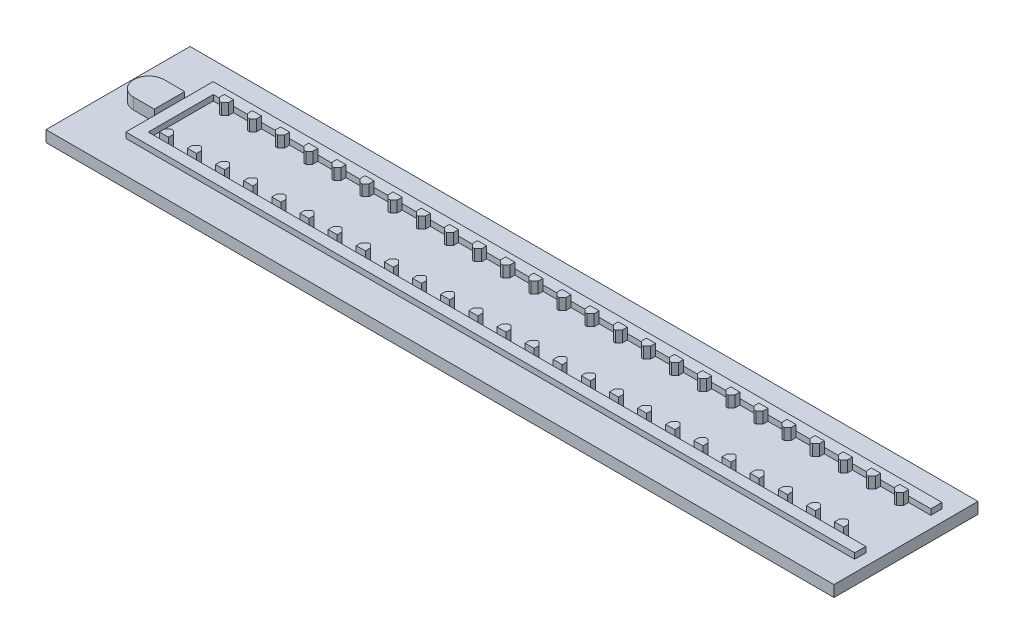
SolidWorks part; units mm, degrees
ref_plane "Front Plane" through (0, 0, 0) normal (0, 0, 1) x (1, 0, 0)
ref_plane "Top Plane" through (0, 0, 0) normal (0, 1, 0) x (1, 0, 0)
ref_plane "Right Plane" through (0, 0, 0) normal (1, 0, 0) x (0, 0, -1)
sketch "Sketch1" plane through (0, 0, 0) normal (0, 1, 0) x (1, 0, 0)
  line L0 (-40.909, -15.5054) -> (218.1261, -15.5054)
  line L1 (-36.909, -11.5614) -> (-32.9778, -11.5614)
  line L2 (-22.9778, -11.5614) -> (-29.7568, -11.5614)
  line L3 (-40.909, 15.5614) -> (218.1261, 15.5614)
  line L4 (-19.7568, -11.5614) -> (-12.9778, -11.5614)
  line L5 (-48.251, -5.3994) -> (-40.909, -5.3994)
  line L6 (-40.909, -5.3994) -> (-40.909, -15.5054)
  line L7 (-48.251, 5.3994) -> (-40.909, 5.3994)
  line L8 (-40.909, 5.3994) -> (-40.909, 15.5614)
  line L9 (-9.7568, -11.5614) -> (-2.9778, -11.5614)
  line L10 (-32.9778, -11.5614) -> (-32.9778, -9.7922)
  line L11 (-32.9778, -9.7922) -> (-31.7373, -8.5518)
  line L12 (-31.7373, -8.5518) -> (-30.9972, -8.5518)
  line L13 (-30.9972, -8.5518) -> (-29.7568, -9.7922)
  line L14 (-29.7568, -9.7922) -> (-29.7568, -11.5614)
  line L15 (-22.9778, -11.5614) -> (-22.9778, -9.7922)
  line L16 (-22.9778, -9.7922) -> (-21.7373, -8.5518)
  line L17 (-21.7373, -8.5518) -> (-20.9972, -8.5518)
  line L18 (-20.9972, -8.5518) -> (-19.7568, -9.7922)
  line L19 (-19.7568, -9.7922) -> (-19.7568, -11.5614)
  line L20 (-12.9778, -11.5614) -> (-12.9778, -9.7922)
  line L21 (-12.9778, -9.7922) -> (-11.7373, -8.5518)
  line L22 (-11.7373, -8.5518) -> (-10.9972, -8.5518)
  line L23 (-10.9972, -8.5518) -> (-9.7568, -9.7922)
  line L24 (-9.7568, -9.7922) -> (-9.7568, -11.5614)
  line L25 (-2.9778, -11.5614) -> (-2.9778, -9.7922)
  line L26 (-2.9778, -9.7922) -> (-1.7373, -8.5518)
  line L27 (-1.7373, -8.5518) -> (-0.9972, -8.5518)
  line L28 (-0.9972, -8.5518) -> (0.2432, -9.7922)
  line L29 (0.2432, -9.7922) -> (0.2432, -11.5614)
  line L30 (7.0222, -11.5614) -> (7.0222, -9.7922)
  line L31 (7.0222, -9.7922) -> (8.2627, -8.5518)
  line L32 (8.2627, -8.5518) -> (9.0028, -8.5518)
  line L33 (9.0028, -8.5518) -> (10.2432, -9.7922)
  line L34 (10.2432, -9.7922) -> (10.2432, -11.5614)
  line L35 (17.0222, -11.5614) -> (17.0222, -9.7922)
  line L36 (17.0222, -9.7922) -> (18.2627, -8.5518)
  line L37 (18.2627, -8.5518) -> (19.0028, -8.5518)
  line L38 (19.0028, -8.5518) -> (20.2432, -9.7922)
  line L39 (20.2432, -9.7922) -> (20.2432, -11.5614)
  line L40 (27.0222, -11.5614) -> (27.0222, -9.7922)
  line L41 (27.0222, -9.7922) -> (28.2627, -8.5518)
  line L42 (28.2627, -8.5518) -> (29.0028, -8.5518)
  line L43 (29.0028, -8.5518) -> (30.2432, -9.7922)
  line L44 (30.2432, -9.7922) -> (30.2432, -11.5614)
  line L45 (37.0222, -11.5614) -> (37.0222, -9.7922)
  line L46 (37.0222, -9.7922) -> (38.2627, -8.5518)
  line L47 (38.2627, -8.5518) -> (39.0028, -8.5518)
  line L48 (39.0028, -8.5518) -> (40.2432, -9.7922)
  line L49 (40.2432, -9.7922) -> (40.2432, -11.5614)
  line L50 (47.0222, -11.5614) -> (47.0222, -9.7922)
  line L51 (47.0222, -9.7922) -> (48.2627, -8.5518)
  line L52 (48.2627, -8.5518) -> (49.0028, -8.5518)
  line L53 (49.0028, -8.5518) -> (50.2432, -9.7922)
  line L54 (50.2432, -9.7922) -> (50.2432, -11.5614)
  line L55 (57.0222, -11.5614) -> (57.0222, -9.7922)
  line L56 (57.0222, -9.7922) -> (58.2627, -8.5518)
  line L57 (58.2627, -8.5518) -> (59.0028, -8.5518)
  line L58 (59.0028, -8.5518) -> (60.2432, -9.7922)
  line L59 (60.2432, -9.7922) -> (60.2432, -11.5614)
  line L60 (67.0222, -11.5614) -> (67.0222, -9.7922)
  line L61 (67.0222, -9.7922) -> (68.2627, -8.5518)
  line L62 (68.2627, -8.5518) -> (69.0028, -8.5518)
  line L63 (69.0028, -8.5518) -> (70.2432, -9.7922)
  line L64 (70.2432, -9.7922) -> (70.2432, -11.5614)
  line L65 (77.0222, -11.5614) -> (77.0222, -9.7922)
  line L66 (77.0222, -9.7922) -> (78.2627, -8.5518)
  line L67 (78.2627, -8.5518) -> (79.0028, -8.5518)
  line L68 (79.0028, -8.5518) -> (80.2432, -9.7922)
  line L69 (80.2432, -9.7922) -> (80.2432, -11.5614)
  line L70 (87.0222, -11.5614) -> (87.0222, -9.7922)
  line L71 (87.0222, -9.7922) -> (88.2627, -8.5518)
  line L72 (88.2627, -8.5518) -> (89.0028, -8.5518)
  line L73 (89.0028, -8.5518) -> (90.2432, -9.7922)
  line L74 (90.2432, -9.7922) -> (90.2432, -11.5614)
  line L75 (97.0222, -11.5614) -> (97.0222, -9.7922)
  line L76 (97.0222, -9.7922) -> (98.2627, -8.5518)
  line L77 (98.2627, -8.5518) -> (99.0028, -8.5518)
  line L78 (99.0028, -8.5518) -> (100.2432, -9.7922)
  line L79 (100.2432, -9.7922) -> (100.2432, -11.5614)
  line L80 (107.0222, -11.5614) -> (107.0222, -9.7922)
  line L81 (107.0222, -9.7922) -> (108.2627, -8.5518)
  line L82 (108.2627, -8.5518) -> (109.0028, -8.5518)
  line L83 (109.0028, -8.5518) -> (110.2432, -9.7922)
  line L84 (110.2432, -9.7922) -> (110.2432, -11.5614)
  line L85 (117.0222, -11.5614) -> (117.0222, -9.7922)
  line L86 (117.0222, -9.7922) -> (118.2627, -8.5518)
  line L87 (118.2627, -8.5518) -> (119.0028, -8.5518)
  line L88 (119.0028, -8.5518) -> (120.2432, -9.7922)
  line L89 (120.2432, -9.7922) -> (120.2432, -11.5614)
  line L90 (127.0222, -11.5614) -> (127.0222, -9.7922)
  line L91 (127.0222, -9.7922) -> (128.2627, -8.5518)
  line L92 (128.2627, -8.5518) -> (129.0028, -8.5518)
  line L93 (129.0028, -8.5518) -> (130.2432, -9.7922)
  line L94 (130.2432, -9.7922) -> (130.2432, -11.5614)
  line L95 (137.0222, -11.5614) -> (137.0222, -9.7922)
  line L96 (137.0222, -9.7922) -> (138.2627, -8.5518)
  line L97 (138.2627, -8.5518) -> (139.0028, -8.5518)
  line L98 (139.0028, -8.5518) -> (140.2432, -9.7922)
  line L99 (140.2432, -9.7922) -> (140.2432, -11.5614)
  line L100 (147.0222, -11.5614) -> (147.0222, -9.7922)
  line L101 (147.0222, -9.7922) -> (148.2627, -8.5518)
  line L102 (148.2627, -8.5518) -> (149.0028, -8.5518)
  line L103 (149.0028, -8.5518) -> (150.2432, -9.7922)
  line L104 (150.2432, -9.7922) -> (150.2432, -11.5614)
  line L105 (157.0222, -11.5614) -> (157.0222, -9.7922)
  line L106 (157.0222, -9.7922) -> (158.2627, -8.5518)
  line L107 (158.2627, -8.5518) -> (159.0028, -8.5518)
  line L108 (159.0028, -8.5518) -> (160.2432, -9.7922)
  line L109 (160.2432, -9.7922) -> (160.2432, -11.5614)
  line L110 (167.0222, -11.5614) -> (167.0222, -9.7922)
  line L111 (167.0222, -9.7922) -> (168.2627, -8.5518)
  line L112 (168.2627, -8.5518) -> (169.0028, -8.5518)
  line L113 (169.0028, -8.5518) -> (170.2432, -9.7922)
  line L114 (170.2432, -9.7922) -> (170.2432, -11.5614)
  line L115 (177.0222, -11.5614) -> (177.0222, -9.7922)
  line L116 (177.0222, -9.7922) -> (178.2627, -8.5518)
  line L117 (178.2627, -8.5518) -> (179.0028, -8.5518)
  line L118 (179.0028, -8.5518) -> (180.2432, -9.7922)
  line L119 (180.2432, -9.7922) -> (180.2432, -11.5614)
  line L120 (187.0222, -11.5614) -> (187.0222, -9.7922)
  line L121 (187.0222, -9.7922) -> (188.2627, -8.5518)
  line L122 (188.2627, -8.5518) -> (189.0028, -8.5518)
  line L123 (189.0028, -8.5518) -> (190.2432, -9.7922)
  line L124 (190.2432, -9.7922) -> (190.2432, -11.5614)
  line L125 (197.0222, -11.5614) -> (197.0222, -9.7922)
  line L126 (197.0222, -9.7922) -> (198.2627, -8.5518)
  line L127 (198.2627, -8.5518) -> (199.0028, -8.5518)
  line L128 (199.0028, -8.5518) -> (200.2432, -9.7922)
  line L129 (200.2432, -9.7922) -> (200.2432, -11.5614)
  line L130 (207.0222, -11.5614) -> (207.0222, -9.7922)
  line L131 (207.0222, -9.7922) -> (208.2627, -8.5518)
  line L132 (208.2627, -8.5518) -> (209.0028, -8.5518)
  line L133 (209.0028, -8.5518) -> (210.2432, -9.7922)
  line L134 (210.2432, -9.7922) -> (210.2432, -11.5614)
  line L135 (218.1261, -11.5614) -> (218.1261, -15.5054)
  line L136 (210.2432, 9.7922) -> (210.2432, 11.5614)
  line L137 (209.0028, 8.5518) -> (210.2432, 9.7922)
  line L138 (208.2627, 8.5518) -> (209.0028, 8.5518)
  line L139 (207.0222, 9.7922) -> (208.2627, 8.5518)
  line L140 (207.0222, 11.5614) -> (207.0222, 9.7922)
  line L141 (200.2432, 9.7922) -> (200.2432, 11.5614)
  line L142 (199.0028, 8.5518) -> (200.2432, 9.7922)
  line L143 (198.2627, 8.5518) -> (199.0028, 8.5518)
  line L144 (197.0222, 9.7922) -> (198.2627, 8.5518)
  line L145 (197.0222, 11.5614) -> (197.0222, 9.7922)
  line L146 (190.2432, 9.7922) -> (190.2432, 11.5614)
  line L147 (189.0028, 8.5518) -> (190.2432, 9.7922)
  line L148 (188.2627, 8.5518) -> (189.0028, 8.5518)
  line L149 (187.0222, 9.7922) -> (188.2627, 8.5518)
  line L150 (187.0222, 11.5614) -> (187.0222, 9.7922)
  line L151 (180.2432, 9.7922) -> (180.2432, 11.5614)
  line L152 (179.0028, 8.5518) -> (180.2432, 9.7922)
  line L153 (178.2627, 8.5518) -> (179.0028, 8.5518)
  line L154 (177.0222, 9.7922) -> (178.2627, 8.5518)
  line L155 (177.0222, 11.5614) -> (177.0222, 9.7922)
  line L156 (170.2432, 9.7922) -> (170.2432, 11.5614)
  line L157 (169.0028, 8.5518) -> (170.2432, 9.7922)
  line L158 (168.2627, 8.5518) -> (169.0028, 8.5518)
  line L159 (167.0222, 9.7922) -> (168.2627, 8.5518)
  line L160 (167.0222, 11.5614) -> (167.0222, 9.7922)
  line L161 (160.2432, 9.7922) -> (160.2432, 11.5614)
  line L162 (159.0028, 8.5518) -> (160.2432, 9.7922)
  line L163 (158.2627, 8.5518) -> (159.0028, 8.5518)
  line L164 (157.0222, 9.7922) -> (158.2627, 8.5518)
  line L165 (157.0222, 11.5614) -> (157.0222, 9.7922)
  line L166 (150.2432, 9.7922) -> (150.2432, 11.5614)
  line L167 (149.0028, 8.5518) -> (150.2432, 9.7922)
  line L168 (148.2627, 8.5518) -> (149.0028, 8.5518)
  line L169 (147.0222, 9.7922) -> (148.2627, 8.5518)
  line L170 (147.0222, 11.5614) -> (147.0222, 9.7922)
  line L171 (140.2432, 9.7922) -> (140.2432, 11.5614)
  line L172 (139.0028, 8.5518) -> (140.2432, 9.7922)
  line L173 (138.2627, 8.5518) -> (139.0028, 8.5518)
  line L174 (137.0222, 9.7922) -> (138.2627, 8.5518)
  line L175 (137.0222, 11.5614) -> (137.0222, 9.7922)
  line L176 (130.2432, 9.7922) -> (130.2432, 11.5614)
  line L177 (129.0028, 8.5518) -> (130.2432, 9.7922)
  line L178 (128.2627, 8.5518) -> (129.0028, 8.5518)
  line L179 (127.0222, 9.7922) -> (128.2627, 8.5518)
  line L180 (127.0222, 11.5614) -> (127.0222, 9.7922)
  line L181 (120.2432, 9.7922) -> (120.2432, 11.5614)
  line L182 (119.0028, 8.5518) -> (120.2432, 9.7922)
  line L183 (118.2627, 8.5518) -> (119.0028, 8.5518)
  line L184 (117.0222, 9.7922) -> (118.2627, 8.5518)
  line L185 (117.0222, 11.5614) -> (117.0222, 9.7922)
  line L186 (110.2432, 9.7922) -> (110.2432, 11.5614)
  line L187 (109.0028, 8.5518) -> (110.2432, 9.7922)
  line L188 (108.2627, 8.5518) -> (109.0028, 8.5518)
  line L189 (107.0222, 9.7922) -> (108.2627, 8.5518)
  line L190 (107.0222, 11.5614) -> (107.0222, 9.7922)
  line L191 (100.2432, 9.7922) -> (100.2432, 11.5614)
  line L192 (99.0028, 8.5518) -> (100.2432, 9.7922)
  line L193 (98.2627, 8.5518) -> (99.0028, 8.5518)
  line L194 (97.0222, 9.7922) -> (98.2627, 8.5518)
  line L195 (97.0222, 11.5614) -> (97.0222, 9.7922)
  line L196 (90.2432, 9.7922) -> (90.2432, 11.5614)
  line L197 (89.0028, 8.5518) -> (90.2432, 9.7922)
  line L198 (88.2627, 8.5518) -> (89.0028, 8.5518)
  line L199 (87.0222, 9.7922) -> (88.2627, 8.5518)
  line L200 (87.0222, 11.5614) -> (87.0222, 9.7922)
  line L201 (80.2432, 9.7922) -> (80.2432, 11.5614)
  line L202 (79.0028, 8.5518) -> (80.2432, 9.7922)
  line L203 (78.2627, 8.5518) -> (79.0028, 8.5518)
  line L204 (77.0222, 9.7922) -> (78.2627, 8.5518)
  line L205 (77.0222, 11.5614) -> (77.0222, 9.7922)
  line L206 (70.2432, 9.7922) -> (70.2432, 11.5614)
  line L207 (69.0028, 8.5518) -> (70.2432, 9.7922)
  line L208 (68.2627, 8.5518) -> (69.0028, 8.5518)
  line L209 (67.0222, 9.7922) -> (68.2627, 8.5518)
  line L210 (67.0222, 11.5614) -> (67.0222, 9.7922)
  line L211 (60.2432, 9.7922) -> (60.2432, 11.5614)
  line L212 (59.0028, 8.5518) -> (60.2432, 9.7922)
  line L213 (58.2627, 8.5518) -> (59.0028, 8.5518)
  line L214 (57.0222, 9.7922) -> (58.2627, 8.5518)
  line L215 (57.0222, 11.5614) -> (57.0222, 9.7922)
  line L216 (50.2432, 9.7922) -> (50.2432, 11.5614)
  line L217 (49.0028, 8.5518) -> (50.2432, 9.7922)
  line L218 (48.2627, 8.5518) -> (49.0028, 8.5518)
  line L219 (47.0222, 9.7922) -> (48.2627, 8.5518)
  line L220 (47.0222, 11.5614) -> (47.0222, 9.7922)
  line L221 (40.2432, 9.7922) -> (40.2432, 11.5614)
  line L222 (39.0028, 8.5518) -> (40.2432, 9.7922)
  line L223 (38.2627, 8.5518) -> (39.0028, 8.5518)
  line L224 (37.0222, 9.7922) -> (38.2627, 8.5518)
  line L225 (37.0222, 11.5614) -> (37.0222, 9.7922)
  line L226 (30.2432, 9.7922) -> (30.2432, 11.5614)
  line L227 (29.0028, 8.5518) -> (30.2432, 9.7922)
  line L228 (28.2627, 8.5518) -> (29.0028, 8.5518)
  line L229 (27.0222, 9.7922) -> (28.2627, 8.5518)
  line L230 (27.0222, 11.5614) -> (27.0222, 9.7922)
  line L231 (20.2432, 9.7922) -> (20.2432, 11.5614)
  line L232 (19.0028, 8.5518) -> (20.2432, 9.7922)
  line L233 (18.2627, 8.5518) -> (19.0028, 8.5518)
  line L234 (17.0222, 9.7922) -> (18.2627, 8.5518)
  line L235 (17.0222, 11.5614) -> (17.0222, 9.7922)
  line L236 (10.2432, 9.7922) -> (10.2432, 11.5614)
  line L237 (9.0028, 8.5518) -> (10.2432, 9.7922)
  line L238 (8.2627, 8.5518) -> (9.0028, 8.5518)
  line L239 (7.0222, 9.7922) -> (8.2627, 8.5518)
  line L240 (7.0222, 11.5614) -> (7.0222, 9.7922)
  line L241 (0.2432, 9.7922) -> (0.2432, 11.5614)
  line L242 (-0.9972, 8.5518) -> (0.2432, 9.7922)
  line L243 (-1.7373, 8.5518) -> (-0.9972, 8.5518)
  line L244 (-2.9778, 9.7922) -> (-1.7373, 8.5518)
  line L245 (-2.9778, 11.5614) -> (-2.9778, 9.7922)
  line L246 (-9.7568, 9.7922) -> (-9.7568, 11.5614)
  line L247 (-10.9972, 8.5518) -> (-9.7568, 9.7922)
  line L248 (-11.7373, 8.5518) -> (-10.9972, 8.5518)
  line L249 (-12.9778, 9.7922) -> (-11.7373, 8.5518)
  line L250 (-12.9778, 11.5614) -> (-12.9778, 9.7922)
  line L251 (-19.7568, 9.7922) -> (-19.7568, 11.5614)
  line L252 (-20.9972, 8.5518) -> (-19.7568, 9.7922)
  line L253 (-21.7373, 8.5518) -> (-20.9972, 8.5518)
  line L254 (-22.9778, 9.7922) -> (-21.7373, 8.5518)
  line L255 (-22.9778, 11.5614) -> (-22.9778, 9.7922)
  line L256 (-29.7568, 9.7922) -> (-29.7568, 11.5614)
  line L257 (-30.9972, 8.5518) -> (-29.7568, 9.7922)
  line L258 (-31.7373, 8.5518) -> (-30.9972, 8.5518)
  line L259 (-32.9778, 9.7922) -> (-31.7373, 8.5518)
  line L260 (-32.9778, 11.5614) -> (-32.9778, 9.7922)
  line L261 (-36.909, 11.5614) -> (-36.909, -11.5614)
  line L262 (-40.909, 5.3994) -> (-40.909, 15.5614)
  line L264 (-40.909, 15.5614) -> (218.1261, 15.5614)
  line L265 (218.1261, 11.5614) -> (218.1261, 15.5614)
  line L266 (-12.9778, -11.5614) -> (-19.7568, -11.5614)
  line L267 (0.2432, -11.5614) -> (7.0222, -11.5614)
  line L268 (-2.9778, -11.5614) -> (-9.7568, -11.5614)
  line L269 (10.2432, -11.5614) -> (17.0222, -11.5614)
  line L270 (7.0222, -11.5614) -> (0.2432, -11.5614)
  line L271 (20.2432, -11.5614) -> (27.0222, -11.5614)
  line L272 (17.0222, -11.5614) -> (10.2432, -11.5614)
  line L273 (30.2432, -11.5614) -> (37.0222, -11.5614)
  line L274 (27.0222, -11.5614) -> (20.2432, -11.5614)
  line L275 (40.2432, -11.5614) -> (47.0222, -11.5614)
  line L276 (37.0222, -11.5614) -> (30.2432, -11.5614)
  line L277 (50.2432, -11.5614) -> (57.0222, -11.5614)
  line L278 (47.0222, -11.5614) -> (40.2432, -11.5614)
  line L279 (60.2432, -11.5614) -> (67.0222, -11.5614)
  line L280 (57.0222, -11.5614) -> (50.2432, -11.5614)
  line L281 (70.2432, -11.5614) -> (77.0222, -11.5614)
  line L282 (67.0222, -11.5614) -> (60.2432, -11.5614)
  line L283 (80.2432, -11.5614) -> (87.0222, -11.5614)
  line L284 (77.0222, -11.5614) -> (70.2432, -11.5614)
  line L285 (90.2432, -11.5614) -> (97.0222, -11.5614)
  line L286 (87.0222, -11.5614) -> (80.2432, -11.5614)
  line L287 (100.2432, -11.5614) -> (107.0222, -11.5614)
  line L288 (97.0222, -11.5614) -> (90.2432, -11.5614)
  line L289 (110.2432, -11.5614) -> (117.0222, -11.5614)
  line L290 (107.0222, -11.5614) -> (100.2432, -11.5614)
  line L291 (120.2432, -11.5614) -> (127.0222, -11.5614)
  line L292 (117.0222, -11.5614) -> (110.2432, -11.5614)
  line L293 (130.2432, -11.5614) -> (137.0222, -11.5614)
  line L294 (127.0222, -11.5614) -> (120.2432, -11.5614)
  line L295 (140.2432, -11.5614) -> (147.0222, -11.5614)
  line L296 (137.0222, -11.5614) -> (130.2432, -11.5614)
  line L297 (150.2432, -11.5614) -> (157.0222, -11.5614)
  line L298 (147.0222, -11.5614) -> (140.2432, -11.5614)
  line L299 (160.2432, -11.5614) -> (167.0222, -11.5614)
  line L300 (157.0222, -11.5614) -> (150.2432, -11.5614)
  line L301 (170.2432, -11.5614) -> (177.0222, -11.5614)
  line L302 (167.0222, -11.5614) -> (160.2432, -11.5614)
  line L303 (180.2432, -11.5614) -> (187.0222, -11.5614)
  line L304 (177.0222, -11.5614) -> (170.2432, -11.5614)
  line L305 (190.2432, -11.5614) -> (197.0222, -11.5614)
  line L306 (187.0222, -11.5614) -> (180.2432, -11.5614)
  line L307 (200.2432, -11.5614) -> (207.0222, -11.5614)
  line L308 (197.0222, -11.5614) -> (190.2432, -11.5614)
  line L309 (210.2432, -11.5614) -> (217.0222, -11.5614)
  line L310 (207.0222, -11.5614) -> (200.2432, -11.5614)
  line L311 (217.0222, -11.5614) -> (218.1261, -11.5614)
  line L312 (217.0222, -11.5614) -> (210.2432, -11.5614)
  line L313 (220.2432, -11.5614) -> (227.0222, -11.5614) [skipped]
  line L315 (217.0222, 11.5054) -> (210.2432, 11.5054)
  line L316 (217.0222, 11.5054) -> (218.1261, 11.5054)
  line L317 (207.0222, 11.5054) -> (200.2432, 11.5054)
  line L318 (210.2432, 11.5054) -> (217.0222, 11.5054)
  line L319 (197.0222, 11.5054) -> (190.2432, 11.5054)
  line L320 (200.2432, 11.5054) -> (207.0222, 11.5054)
  line L321 (187.0222, 11.5054) -> (180.2432, 11.5054)
  line L322 (190.2432, 11.5054) -> (197.0222, 11.5054)
  line L323 (177.0222, 11.5054) -> (170.2432, 11.5054)
  line L324 (180.2432, 11.5054) -> (187.0222, 11.5054)
  line L325 (167.0222, 11.5054) -> (160.2432, 11.5054)
  line L326 (170.2432, 11.5054) -> (177.0222, 11.5054)
  line L327 (157.0222, 11.5054) -> (150.2432, 11.5054)
  line L328 (160.2432, 11.5054) -> (167.0222, 11.5054)
  line L329 (147.0222, 11.5054) -> (140.2432, 11.5054)
  line L330 (150.2432, 11.5054) -> (157.0222, 11.5054)
  line L331 (137.0222, 11.5054) -> (130.2432, 11.5054)
  line L332 (140.2432, 11.5054) -> (147.0222, 11.5054)
  line L333 (127.0222, 11.5054) -> (120.2432, 11.5054)
  line L334 (130.2432, 11.5054) -> (137.0222, 11.5054)
  line L335 (117.0222, 11.5054) -> (110.2432, 11.5054)
  line L336 (120.2432, 11.5054) -> (127.0222, 11.5054)
  line L337 (107.0222, 11.5054) -> (100.2432, 11.5054)
  line L338 (110.2432, 11.5054) -> (117.0222, 11.5054)
  line L339 (97.0222, 11.5054) -> (90.2432, 11.5054)
  line L340 (100.2432, 11.5054) -> (107.0222, 11.5054)
  line L341 (87.0222, 11.5054) -> (80.2432, 11.5054)
  line L342 (90.2432, 11.5054) -> (97.0222, 11.5054)
  line L343 (77.0222, 11.5054) -> (70.2432, 11.5054)
  line L344 (80.2432, 11.5054) -> (87.0222, 11.5054)
  line L345 (67.0222, 11.5054) -> (60.2432, 11.5054)
  line L346 (70.2432, 11.5054) -> (77.0222, 11.5054)
  line L347 (57.0222, 11.5054) -> (50.2432, 11.5054)
  line L348 (60.2432, 11.5054) -> (67.0222, 11.5054)
  line L349 (47.0222, 11.5054) -> (40.2432, 11.5054)
  line L350 (50.2432, 11.5054) -> (57.0222, 11.5054)
  line L351 (37.0222, 11.5054) -> (30.2432, 11.5054)
  line L352 (40.2432, 11.5054) -> (47.0222, 11.5054)
  line L353 (27.0222, 11.5054) -> (20.2432, 11.5054)
  line L354 (30.2432, 11.5054) -> (37.0222, 11.5054)
  line L355 (17.0222, 11.5054) -> (10.2432, 11.5054)
  line L356 (20.2432, 11.5054) -> (27.0222, 11.5054)
  line L357 (7.0222, 11.5054) -> (0.2432, 11.5054)
  line L358 (10.2432, 11.5054) -> (17.0222, 11.5054)
  line L359 (-2.9778, 11.5054) -> (-9.7568, 11.5054)
  line L360 (0.2432, 11.5054) -> (7.0222, 11.5054)
  line L361 (-12.9778, 11.5054) -> (-19.7568, 11.5054)
  line L362 (-36.909, -11.5614) -> (-36.909, 11.5054)
  line L363 (218.1261, 11.5054) -> (218.1261, 15.5054)
  line L364 (210.2432, 9.7922) -> (210.2432, 11.5054)
  line L365 (209.0028, 8.5518) -> (210.2432, 9.7922)
  line L366 (208.2627, 8.5518) -> (209.0028, 8.5518)
  line L367 (207.0222, 9.7922) -> (208.2627, 8.5518)
  line L368 (207.0222, 11.5054) -> (207.0222, 9.7922)
  line L369 (200.2432, 9.7922) -> (200.2432, 11.5054)
  line L370 (199.0028, 8.5518) -> (200.2432, 9.7922)
  line L371 (198.2627, 8.5518) -> (199.0028, 8.5518)
  line L372 (197.0222, 9.7922) -> (198.2627, 8.5518)
  line L373 (197.0222, 11.5054) -> (197.0222, 9.7922)
  line L374 (190.2432, 9.7922) -> (190.2432, 11.5054)
  line L375 (189.0028, 8.5518) -> (190.2432, 9.7922)
  line L376 (188.2627, 8.5518) -> (189.0028, 8.5518)
  line L377 (187.0222, 9.7922) -> (188.2627, 8.5518)
  line L378 (187.0222, 11.5054) -> (187.0222, 9.7922)
  line L379 (180.2432, 9.7922) -> (180.2432, 11.5054)
  line L380 (179.0028, 8.5518) -> (180.2432, 9.7922)
  line L381 (178.2627, 8.5518) -> (179.0028, 8.5518)
  line L382 (177.0222, 9.7922) -> (178.2627, 8.5518)
  line L383 (177.0222, 11.5054) -> (177.0222, 9.7922)
  line L384 (170.2432, 9.7922) -> (170.2432, 11.5054)
  line L385 (169.0028, 8.5518) -> (170.2432, 9.7922)
  line L386 (168.2627, 8.5518) -> (169.0028, 8.5518)
  line L387 (167.0222, 9.7922) -> (168.2627, 8.5518)
  line L388 (167.0222, 11.5054) -> (167.0222, 9.7922)
  line L389 (160.2432, 9.7922) -> (160.2432, 11.5054)
  line L390 (159.0028, 8.5518) -> (160.2432, 9.7922)
  line L391 (158.2627, 8.5518) -> (159.0028, 8.5518)
  line L392 (157.0222, 9.7922) -> (158.2627, 8.5518)
  line L393 (157.0222, 11.5054) -> (157.0222, 9.7922)
  line L394 (150.2432, 9.7922) -> (150.2432, 11.5054)
  line L395 (149.0028, 8.5518) -> (150.2432, 9.7922)
  line L396 (148.2627, 8.5518) -> (149.0028, 8.5518)
  line L397 (147.0222, 9.7922) -> (148.2627, 8.5518)
  line L398 (147.0222, 11.5054) -> (147.0222, 9.7922)
  line L399 (140.2432, 9.7922) -> (140.2432, 11.5054)
  line L400 (139.0028, 8.5518) -> (140.2432, 9.7922)
  line L401 (138.2627, 8.5518) -> (139.0028, 8.5518)
  line L402 (137.0222, 9.7922) -> (138.2627, 8.5518)
  line L403 (137.0222, 11.5054) -> (137.0222, 9.7922)
  line L404 (130.2432, 9.7922) -> (130.2432, 11.5054)
  line L405 (129.0028, 8.5518) -> (130.2432, 9.7922)
  line L406 (128.2627, 8.5518) -> (129.0028, 8.5518)
  line L407 (127.0222, 9.7922) -> (128.2627, 8.5518)
  line L408 (127.0222, 11.5054) -> (127.0222, 9.7922)
  line L409 (120.2432, 9.7922) -> (120.2432, 11.5054)
  line L410 (119.0028, 8.5518) -> (120.2432, 9.7922)
  line L411 (118.2627, 8.5518) -> (119.0028, 8.5518)
  line L412 (117.0222, 9.7922) -> (118.2627, 8.5518)
  line L413 (117.0222, 11.5054) -> (117.0222, 9.7922)
  line L414 (110.2432, 9.7922) -> (110.2432, 11.5054)
  line L415 (109.0028, 8.5518) -> (110.2432, 9.7922)
  line L416 (108.2627, 8.5518) -> (109.0028, 8.5518)
  line L417 (107.0222, 9.7922) -> (108.2627, 8.5518)
  line L418 (107.0222, 11.5054) -> (107.0222, 9.7922)
  line L419 (100.2432, 9.7922) -> (100.2432, 11.5054)
  line L420 (99.0028, 8.5518) -> (100.2432, 9.7922)
  line L421 (98.2627, 8.5518) -> (99.0028, 8.5518)
  line L422 (97.0222, 9.7922) -> (98.2627, 8.5518)
  line L423 (97.0222, 11.5054) -> (97.0222, 9.7922)
  line L424 (90.2432, 9.7922) -> (90.2432, 11.5054)
  line L425 (89.0028, 8.5518) -> (90.2432, 9.7922)
  line L426 (88.2627, 8.5518) -> (89.0028, 8.5518)
  line L427 (87.0222, 9.7922) -> (88.2627, 8.5518)
  line L428 (87.0222, 11.5054) -> (87.0222, 9.7922)
  line L429 (80.2432, 9.7922) -> (80.2432, 11.5054)
  line L430 (79.0028, 8.5518) -> (80.2432, 9.7922)
  line L431 (78.2627, 8.5518) -> (79.0028, 8.5518)
  line L432 (77.0222, 9.7922) -> (78.2627, 8.5518)
  line L433 (77.0222, 11.5054) -> (77.0222, 9.7922)
  line L434 (70.2432, 9.7922) -> (70.2432, 11.5054)
  line L435 (69.0028, 8.5518) -> (70.2432, 9.7922)
  line L436 (68.2627, 8.5518) -> (69.0028, 8.5518)
  line L437 (67.0222, 9.7922) -> (68.2627, 8.5518)
  line L438 (67.0222, 11.5054) -> (67.0222, 9.7922)
  line L439 (60.2432, 9.7922) -> (60.2432, 11.5054)
  line L440 (59.0028, 8.5518) -> (60.2432, 9.7922)
  line L441 (58.2627, 8.5518) -> (59.0028, 8.5518)
  line L442 (57.0222, 9.7922) -> (58.2627, 8.5518)
  line L443 (57.0222, 11.5054) -> (57.0222, 9.7922)
  line L444 (50.2432, 9.7922) -> (50.2432, 11.5054)
  line L445 (49.0028, 8.5518) -> (50.2432, 9.7922)
  line L446 (48.2627, 8.5518) -> (49.0028, 8.5518)
  line L447 (47.0222, 9.7922) -> (48.2627, 8.5518)
  line L448 (47.0222, 11.5054) -> (47.0222, 9.7922)
  line L449 (40.2432, 9.7922) -> (40.2432, 11.5054)
  line L450 (39.0028, 8.5518) -> (40.2432, 9.7922)
  line L451 (38.2627, 8.5518) -> (39.0028, 8.5518)
  line L452 (37.0222, 9.7922) -> (38.2627, 8.5518)
  line L453 (37.0222, 11.5054) -> (37.0222, 9.7922)
  line L454 (30.2432, 9.7922) -> (30.2432, 11.5054)
  line L455 (29.0028, 8.5518) -> (30.2432, 9.7922)
  line L456 (28.2627, 8.5518) -> (29.0028, 8.5518)
  line L457 (27.0222, 9.7922) -> (28.2627, 8.5518)
  line L458 (27.0222, 11.5054) -> (27.0222, 9.7922)
  line L459 (20.2432, 9.7922) -> (20.2432, 11.5054)
  line L460 (19.0028, 8.5518) -> (20.2432, 9.7922)
  line L461 (18.2627, 8.5518) -> (19.0028, 8.5518)
  line L462 (17.0222, 9.7922) -> (18.2627, 8.5518)
  line L463 (17.0222, 11.5054) -> (17.0222, 9.7922)
  line L464 (10.2432, 9.7922) -> (10.2432, 11.5054)
  line L465 (9.0028, 8.5518) -> (10.2432, 9.7922)
  line L466 (8.2627, 8.5518) -> (9.0028, 8.5518)
  line L467 (7.0222, 9.7922) -> (8.2627, 8.5518)
  line L468 (7.0222, 11.5054) -> (7.0222, 9.7922)
  line L469 (0.2432, 9.7922) -> (0.2432, 11.5054)
  line L470 (-0.9972, 8.5518) -> (0.2432, 9.7922)
  line L471 (-1.7373, 8.5518) -> (-0.9972, 8.5518)
  line L472 (-2.9778, 9.7922) -> (-1.7373, 8.5518)
  line L473 (-2.9778, 11.5054) -> (-2.9778, 9.7922)
  line L474 (-9.7568, 9.7922) -> (-9.7568, 11.5054)
  line L475 (-10.9972, 8.5518) -> (-9.7568, 9.7922)
  line L476 (-11.7373, 8.5518) -> (-10.9972, 8.5518)
  line L477 (-12.9778, 9.7922) -> (-11.7373, 8.5518)
  line L478 (-12.9778, 11.5054) -> (-12.9778, 9.7922)
  line L479 (-19.7568, 9.7922) -> (-19.7568, 11.5054)
  line L480 (-20.9972, 8.5518) -> (-19.7568, 9.7922)
  line L481 (-21.7373, 8.5518) -> (-20.9972, 8.5518)
  line L482 (-22.9778, 9.7922) -> (-21.7373, 8.5518)
  line L483 (-22.9778, 11.5054) -> (-22.9778, 9.7922)
  line L484 (-29.7568, 9.7922) -> (-29.7568, 11.5054)
  line L485 (-30.9972, 8.5518) -> (-29.7568, 9.7922)
  line L486 (-31.7373, 8.5518) -> (-30.9972, 8.5518)
  line L487 (-32.9778, 9.7922) -> (-31.7373, 8.5518)
  line L488 (-32.9778, 11.5054) -> (-32.9778, 9.7922)
  line L489 (-9.7568, 11.5054) -> (-2.9778, 11.5054)
  line L490 (-40.909, 5.3994) -> (-40.909, 15.5054)
  line L491 (-19.7568, 11.5054) -> (-12.9778, 11.5054)
  line L492 (-22.9778, 11.5054) -> (-29.7568, 11.5054)
  line L493 (-36.909, 11.5054) -> (-32.9778, 11.5054)
  line L494 (-40.909, 15.5054) -> (218.1261, 15.5054)
  line L495 (-36.909, 11.5614) -> (-36.909, -11.5054)
  line L496 (217.0222, 11.5614) -> (210.2432, 11.5614)
  line L497 (217.0222, 11.5614) -> (218.1261, 11.5614)
  line L498 (207.0222, 11.5614) -> (200.2432, 11.5614)
  line L499 (210.2432, 11.5614) -> (217.0222, 11.5614)
  line L500 (197.0222, 11.5614) -> (190.2432, 11.5614)
  line L501 (200.2432, 11.5614) -> (207.0222, 11.5614)
  line L502 (187.0222, 11.5614) -> (180.2432, 11.5614)
  line L503 (190.2432, 11.5614) -> (197.0222, 11.5614)
  line L504 (177.0222, 11.5614) -> (170.2432, 11.5614)
  line L505 (180.2432, 11.5614) -> (187.0222, 11.5614)
  line L506 (167.0222, 11.5614) -> (160.2432, 11.5614)
  line L507 (170.2432, 11.5614) -> (177.0222, 11.5614)
  line L508 (157.0222, 11.5614) -> (150.2432, 11.5614)
  line L509 (160.2432, 11.5614) -> (167.0222, 11.5614)
  line L510 (147.0222, 11.5614) -> (140.2432, 11.5614)
  line L511 (150.2432, 11.5614) -> (157.0222, 11.5614)
  line L512 (137.0222, 11.5614) -> (130.2432, 11.5614)
  line L513 (140.2432, 11.5614) -> (147.0222, 11.5614)
  line L514 (127.0222, 11.5614) -> (120.2432, 11.5614)
  line L515 (130.2432, 11.5614) -> (137.0222, 11.5614)
  line L516 (117.0222, 11.5614) -> (110.2432, 11.5614)
  line L517 (120.2432, 11.5614) -> (127.0222, 11.5614)
  line L518 (107.0222, 11.5614) -> (100.2432, 11.5614)
  line L519 (110.2432, 11.5614) -> (117.0222, 11.5614)
  line L520 (97.0222, 11.5614) -> (90.2432, 11.5614)
  line L521 (100.2432, 11.5614) -> (107.0222, 11.5614)
  line L522 (87.0222, 11.5614) -> (80.2432, 11.5614)
  line L523 (90.2432, 11.5614) -> (97.0222, 11.5614)
  line L524 (77.0222, 11.5614) -> (70.2432, 11.5614)
  line L525 (80.2432, 11.5614) -> (87.0222, 11.5614)
  line L526 (67.0222, 11.5614) -> (60.2432, 11.5614)
  line L527 (70.2432, 11.5614) -> (77.0222, 11.5614)
  line L528 (57.0222, 11.5614) -> (50.2432, 11.5614)
  line L529 (60.2432, 11.5614) -> (67.0222, 11.5614)
  line L530 (47.0222, 11.5614) -> (40.2432, 11.5614)
  line L531 (50.2432, 11.5614) -> (57.0222, 11.5614)
  line L532 (37.0222, 11.5614) -> (30.2432, 11.5614)
  line L533 (40.2432, 11.5614) -> (47.0222, 11.5614)
  line L534 (27.0222, 11.5614) -> (20.2432, 11.5614)
  line L535 (30.2432, 11.5614) -> (37.0222, 11.5614)
  line L536 (17.0222, 11.5614) -> (10.2432, 11.5614)
  line L537 (20.2432, 11.5614) -> (27.0222, 11.5614)
  line L538 (7.0222, 11.5614) -> (0.2432, 11.5614)
  line L539 (10.2432, 11.5614) -> (17.0222, 11.5614)
  line L540 (-2.9778, 11.5614) -> (-9.7568, 11.5614)
  line L541 (0.2432, 11.5614) -> (7.0222, 11.5614)
  line L542 (-12.9778, 11.5614) -> (-19.7568, 11.5614)
  line L543 (218.1261, 11.5614) -> (218.1261, 15.5054)
  line L544 (210.2432, 9.7922) -> (210.2432, 11.5614)
  line L545 (209.0028, 8.5518) -> (210.2432, 9.7922)
  line L546 (208.2627, 8.5518) -> (209.0028, 8.5518)
  line L547 (207.0222, 9.7922) -> (208.2627, 8.5518)
  line L548 (207.0222, 11.5614) -> (207.0222, 9.7922)
  line L549 (200.2432, 9.7922) -> (200.2432, 11.5614)
  line L550 (199.0028, 8.5518) -> (200.2432, 9.7922)
  line L551 (198.2627, 8.5518) -> (199.0028, 8.5518)
  line L552 (197.0222, 9.7922) -> (198.2627, 8.5518)
  line L553 (197.0222, 11.5614) -> (197.0222, 9.7922)
  line L554 (190.2432, 9.7922) -> (190.2432, 11.5614)
  line L555 (189.0028, 8.5518) -> (190.2432, 9.7922)
  line L556 (188.2627, 8.5518) -> (189.0028, 8.5518)
  line L557 (187.0222, 9.7922) -> (188.2627, 8.5518)
  line L558 (187.0222, 11.5614) -> (187.0222, 9.7922)
  line L559 (180.2432, 9.7922) -> (180.2432, 11.5614)
  line L560 (179.0028, 8.5518) -> (180.2432, 9.7922)
  line L561 (178.2627, 8.5518) -> (179.0028, 8.5518)
  line L562 (177.0222, 9.7922) -> (178.2627, 8.5518)
  line L563 (177.0222, 11.5614) -> (177.0222, 9.7922)
  line L564 (170.2432, 9.7922) -> (170.2432, 11.5614)
  line L565 (169.0028, 8.5518) -> (170.2432, 9.7922)
  line L566 (168.2627, 8.5518) -> (169.0028, 8.5518)
  line L567 (167.0222, 9.7922) -> (168.2627, 8.5518)
  line L568 (167.0222, 11.5614) -> (167.0222, 9.7922)
  line L569 (160.2432, 9.7922) -> (160.2432, 11.5614)
  line L570 (159.0028, 8.5518) -> (160.2432, 9.7922)
  line L571 (158.2627, 8.5518) -> (159.0028, 8.5518)
  line L572 (157.0222, 9.7922) -> (158.2627, 8.5518)
  line L573 (157.0222, 11.5614) -> (157.0222, 9.7922)
  line L574 (150.2432, 9.7922) -> (150.2432, 11.5614)
  line L575 (149.0028, 8.5518) -> (150.2432, 9.7922)
  line L576 (148.2627, 8.5518) -> (149.0028, 8.5518)
  line L577 (147.0222, 9.7922) -> (148.2627, 8.5518)
  line L578 (147.0222, 11.5614) -> (147.0222, 9.7922)
  line L579 (140.2432, 9.7922) -> (140.2432, 11.5614)
  line L580 (139.0028, 8.5518) -> (140.2432, 9.7922)
  line L581 (138.2627, 8.5518) -> (139.0028, 8.5518)
  line L582 (137.0222, 9.7922) -> (138.2627, 8.5518)
  line L583 (137.0222, 11.5614) -> (137.0222, 9.7922)
  line L584 (130.2432, 9.7922) -> (130.2432, 11.5614)
  line L585 (129.0028, 8.5518) -> (130.2432, 9.7922)
  line L586 (128.2627, 8.5518) -> (129.0028, 8.5518)
  line L587 (127.0222, 9.7922) -> (128.2627, 8.5518)
  line L588 (127.0222, 11.5614) -> (127.0222, 9.7922)
  line L589 (120.2432, 9.7922) -> (120.2432, 11.5614)
  line L590 (119.0028, 8.5518) -> (120.2432, 9.7922)
  line L591 (118.2627, 8.5518) -> (119.0028, 8.5518)
  line L592 (117.0222, 9.7922) -> (118.2627, 8.5518)
  line L593 (117.0222, 11.5614) -> (117.0222, 9.7922)
  line L594 (110.2432, 9.7922) -> (110.2432, 11.5614)
  line L595 (109.0028, 8.5518) -> (110.2432, 9.7922)
  line L596 (108.2627, 8.5518) -> (109.0028, 8.5518)
  line L597 (107.0222, 9.7922) -> (108.2627, 8.5518)
  line L598 (107.0222, 11.5614) -> (107.0222, 9.7922)
  line L599 (100.2432, 9.7922) -> (100.2432, 11.5614)
  line L600 (99.0028, 8.5518) -> (100.2432, 9.7922)
  line L601 (98.2627, 8.5518) -> (99.0028, 8.5518)
  line L602 (97.0222, 9.7922) -> (98.2627, 8.5518)
  line L603 (97.0222, 11.5614) -> (97.0222, 9.7922)
  line L604 (90.2432, 9.7922) -> (90.2432, 11.5614)
  line L605 (89.0028, 8.5518) -> (90.2432, 9.7922)
  line L606 (88.2627, 8.5518) -> (89.0028, 8.5518)
  line L607 (87.0222, 9.7922) -> (88.2627, 8.5518)
  line L608 (87.0222, 11.5614) -> (87.0222, 9.7922)
  line L609 (80.2432, 9.7922) -> (80.2432, 11.5614)
  line L610 (79.0028, 8.5518) -> (80.2432, 9.7922)
  line L611 (78.2627, 8.5518) -> (79.0028, 8.5518)
  line L612 (77.0222, 9.7922) -> (78.2627, 8.5518)
  line L613 (77.0222, 11.5614) -> (77.0222, 9.7922)
  line L614 (70.2432, 9.7922) -> (70.2432, 11.5614)
  line L615 (69.0028, 8.5518) -> (70.2432, 9.7922)
  line L616 (68.2627, 8.5518) -> (69.0028, 8.5518)
  line L617 (67.0222, 9.7922) -> (68.2627, 8.5518)
  line L618 (67.0222, 11.5614) -> (67.0222, 9.7922)
  line L619 (60.2432, 9.7922) -> (60.2432, 11.5614)
  line L620 (59.0028, 8.5518) -> (60.2432, 9.7922)
  line L621 (58.2627, 8.5518) -> (59.0028, 8.5518)
  line L622 (57.0222, 9.7922) -> (58.2627, 8.5518)
  line L623 (57.0222, 11.5614) -> (57.0222, 9.7922)
  line L624 (50.2432, 9.7922) -> (50.2432, 11.5614)
  line L625 (49.0028, 8.5518) -> (50.2432, 9.7922)
  line L626 (48.2627, 8.5518) -> (49.0028, 8.5518)
  line L627 (47.0222, 9.7922) -> (48.2627, 8.5518)
  line L628 (47.0222, 11.5614) -> (47.0222, 9.7922)
  line L629 (40.2432, 9.7922) -> (40.2432, 11.5614)
  line L630 (39.0028, 8.5518) -> (40.2432, 9.7922)
  line L631 (38.2627, 8.5518) -> (39.0028, 8.5518)
  line L632 (37.0222, 9.7922) -> (38.2627, 8.5518)
  line L633 (37.0222, 11.5614) -> (37.0222, 9.7922)
  line L634 (30.2432, 9.7922) -> (30.2432, 11.5614)
  line L635 (29.0028, 8.5518) -> (30.2432, 9.7922)
  line L636 (28.2627, 8.5518) -> (29.0028, 8.5518)
  line L637 (27.0222, 9.7922) -> (28.2627, 8.5518)
  line L638 (27.0222, 11.5614) -> (27.0222, 9.7922)
  line L639 (20.2432, 9.7922) -> (20.2432, 11.5614)
  line L640 (19.0028, 8.5518) -> (20.2432, 9.7922)
  line L641 (18.2627, 8.5518) -> (19.0028, 8.5518)
  line L642 (17.0222, 9.7922) -> (18.2627, 8.5518)
  line L643 (17.0222, 11.5614) -> (17.0222, 9.7922)
  line L644 (10.2432, 9.7922) -> (10.2432, 11.5614)
  line L645 (9.0028, 8.5518) -> (10.2432, 9.7922)
  line L646 (8.2627, 8.5518) -> (9.0028, 8.5518)
  line L647 (7.0222, 9.7922) -> (8.2627, 8.5518)
  line L648 (7.0222, 11.5614) -> (7.0222, 9.7922)
  line L649 (0.2432, 9.7922) -> (0.2432, 11.5614)
  line L650 (-0.9972, 8.5518) -> (0.2432, 9.7922)
  line L651 (-1.7373, 8.5518) -> (-0.9972, 8.5518)
  line L652 (-2.9778, 9.7922) -> (-1.7373, 8.5518)
  line L653 (-2.9778, 11.5614) -> (-2.9778, 9.7922)
  line L654 (-9.7568, 9.7922) -> (-9.7568, 11.5614)
  line L655 (-10.9972, 8.5518) -> (-9.7568, 9.7922)
  line L656 (-11.7373, 8.5518) -> (-10.9972, 8.5518)
  line L657 (-12.9778, 9.7922) -> (-11.7373, 8.5518)
  line L658 (-12.9778, 11.5614) -> (-12.9778, 9.7922)
  line L659 (-19.7568, 9.7922) -> (-19.7568, 11.5614)
  line L660 (-20.9972, 8.5518) -> (-19.7568, 9.7922)
  line L661 (-21.7373, 8.5518) -> (-20.9972, 8.5518)
  line L662 (-22.9778, 9.7922) -> (-21.7373, 8.5518)
  line L663 (-22.9778, 11.5614) -> (-22.9778, 9.7922)
  line L664 (-29.7568, 9.7922) -> (-29.7568, 11.5614)
  line L665 (-30.9972, 8.5518) -> (-29.7568, 9.7922)
  line L666 (-31.7373, 8.5518) -> (-30.9972, 8.5518)
  line L667 (-32.9778, 9.7922) -> (-31.7373, 8.5518)
  line L668 (-32.9778, 11.5614) -> (-32.9778, 9.7922)
  line L669 (-9.7568, 11.5614) -> (-2.9778, 11.5614)
  line L670 (-40.909, 5.3994) -> (-40.909, 15.5054)
  line L671 (-48.251, 5.3994) -> (-40.909, 5.3994)
  line L672 (-19.7568, 11.5614) -> (-12.9778, 11.5614)
  line L673 (-22.9778, 11.5614) -> (-29.7568, 11.5614)
  line L674 (-36.909, 11.5614) -> (-32.9778, 11.5614)
  line L675 (-40.909, 15.5054) -> (218.1261, 15.5054)
  circle A1 centre (-48.251, 0) radius 5.3994
  dimension "D1" = 25
  dimension "D3" = 25
extrude "Boss-Extrude6" add sketch "Sketch1" along normal blind 4 contours A1 | A1 L5 L6 L0 L135 L311 L309 L134 L133 L132 L131 L130 L307 L129 L128 L127 L126 L125 L305 L124 L123 L122 L121 L120 L303 L119 L118 L117 L116 L115 L301 L114 L113 L112 L111 L110 L299 L109 L108 L107 L106 L105 L297 L104 L103 L102 L101 L100 L295 L99 L98
sketch "Sketch2" plane through (0, 4, 0) normal (0, 1, 0) x (1, 0, 0)
  line L0 (-40.909, 15.5054) -> (218.1261, 15.5054)
  line L1 (-40.909, 15.5054) -> (218.1261, 15.5054) construction
  line L2 (218.1261, 15.5054) -> (218.1261, 11.5614)
  line L3 (218.1261, 11.5614) -> (-36.909, 11.5614)
  line L4 (-36.909, 11.5614) -> (-36.909, -11.5614)
  line L5 (-36.909, -11.5614) -> (-32.9778, -11.5614) construction
  line L6 (-36.909, 11.5614) -> (-36.909, -11.5614) construction
  line L7 (-36.909, -11.5614) -> (218.1261, -11.5614)
  line L8 (218.1261, -11.5614) -> (218.1261, -15.5054)
  line L9 (218.1261, -11.5614) -> (218.1261, -15.5054) construction
  line L10 (-40.909, -15.5054) -> (218.1261, -15.5054) construction
  line L11 (218.1261, -15.5054) -> (-40.909, -15.5054)
  line L12 (-40.909, -15.5054) -> (-40.909, 15.5054)
extrude "Cut-Extrude1" cut sketch "Sketch2" against normal blind 2
ref_plane "Plane1" through (-29.7568, 0, 11.5614) normal (0, -1, 0) x (-1, 0, 0)
sketch "Sketch3" plane through (-29.7568, 0, 11.5614) normal (0, -1, 0) x (1, 0, 0)
  line L0 (-28.0872, -35.7858) -> (251.9822, -35.7858)
  line L1 (251.9822, -35.7858) -> (251.9822, 15.3993)
  line L2 (251.9822, 15.3993) -> (-28.0872, 15.3993)
  line L3 (-28.0872, 15.3993) -> (-28.0872, -34.1762)
  line L4 (-28.0872, -34.1762) -> (-28.0872, -35.7858)
extrude "Boss-Extrude7" add sketch "Sketch3" along normal blind 4
